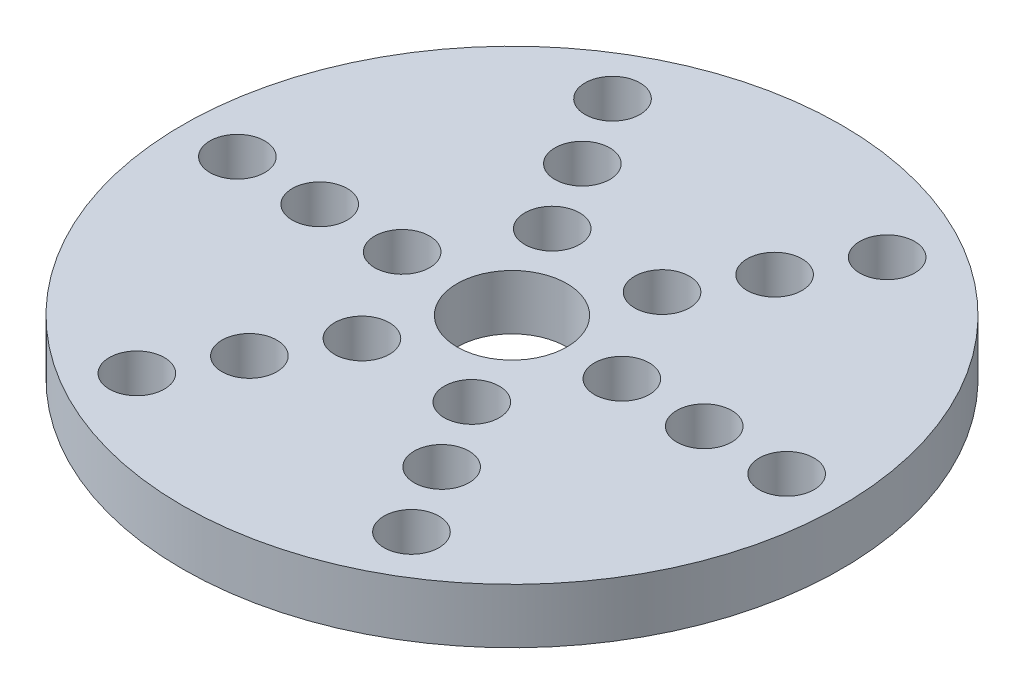
SolidWorks part; units mm, degrees
ref_plane "Front Plane" through (0, 0, 0) normal (0, 0, 1) x (1, 0, 0)
ref_plane "Top Plane" through (0, 0, 0) normal (0, 1, 0) x (1, 0, 0)
ref_plane "Right Plane" through (0, 0, 0) normal (1, 0, 0) x (0, 0, -1)
sketch "Sketch1" plane through (0, 0, 0) normal (0, 1, 0) x (1, 0, 0)
  line L0 (0, -60) -> (0, 60) construction
  line L1 (-60, 0) -> (60, 0) construction
  line L2 (30, -51.9615) -> (-30, 51.9615) construction
  line L3 (-30, -51.9615) -> (30, 51.9615) construction
  circle A0 centre (0, 0) radius 60
  circle A1 centre (0, 0) radius 10
  circle A2 centre (20, 0) radius 5
  circle A3 centre (35, 0) radius 5
  circle A4 centre (50, 0) radius 5
  circle A5 centre (10, -17.3205) radius 5
  circle A6 centre (17.5, -30.3109) radius 5
  circle A7 centre (25, -43.3013) radius 5
  circle A8 centre (-10, -17.3205) radius 5
  circle A9 centre (-17.5, -30.3109) radius 5
  circle A10 centre (-25, -43.3013) radius 5
  circle A11 centre (-20, 0) radius 5
  circle A12 centre (-35, 0) radius 5
  circle A13 centre (-50, 0) radius 5
  circle A14 centre (-10, 17.3205) radius 5
  circle A15 centre (-17.5, 30.3109) radius 5
  circle A16 centre (-25, 43.3013) radius 5
  circle A17 centre (10, 17.3205) radius 5
  circle A18 centre (17.5, 30.3109) radius 5
  circle A19 centre (25, 43.3013) radius 5
  point P47 (0, 0)
  dimension "D1" = 120
  dimension "D2" = 20
  dimension "D3" = 10
  dimension "D4" = 10
  dimension "D5" = 10
  dimension "D6" = 20
  dimension "D7" = 35
  dimension "D8" = 50
  dimension "D10" = 60
  dimension "D12" = 50
  dimension "D9" = 6
extrude "Boss-Extrude1" add sketch "Sketch1" along normal blind 10
